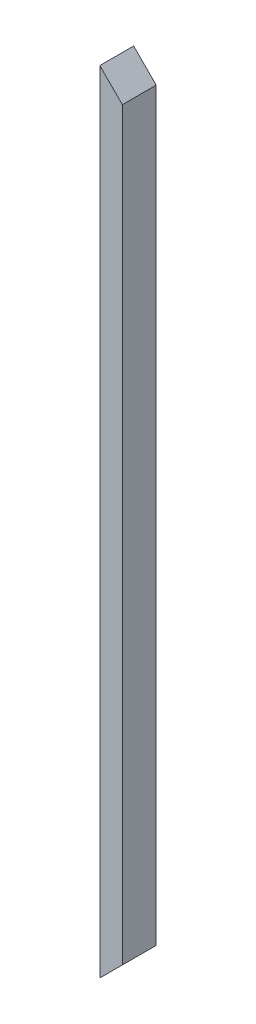
SolidWorks part; units mm, degrees
ref_plane "Plan de face" through (0, 0, 0) normal (0, 0, 1) x (1, 0, 0)
ref_plane "Plan de dessus" through (0, 0, 0) normal (0, 1, 0) x (1, 0, 0)
ref_plane "Plan de droite" through (0, 0, 0) normal (1, 0, 0) x (0, 0, -1)
sketch "Esquisse1" plane through (0, 0, 0) normal (0, 0, 1) x (1, 0, 0)
  line L0 (-350, 350) -> (-350, -350)
  line L1 (-350, -350) -> (-330, -330)
  line L2 (-330, -330) -> (-330, 330)
  line L3 (-330, 330) -> (-350, 350)
  point P4 (-314.9051, -306.1442)
  dimension "D1" = 45
  dimension "D2" = 45
  dimension "D3" = 20
extrude "Boss.-Extru.1" add sketch "Esquisse1" along normal blind 30
